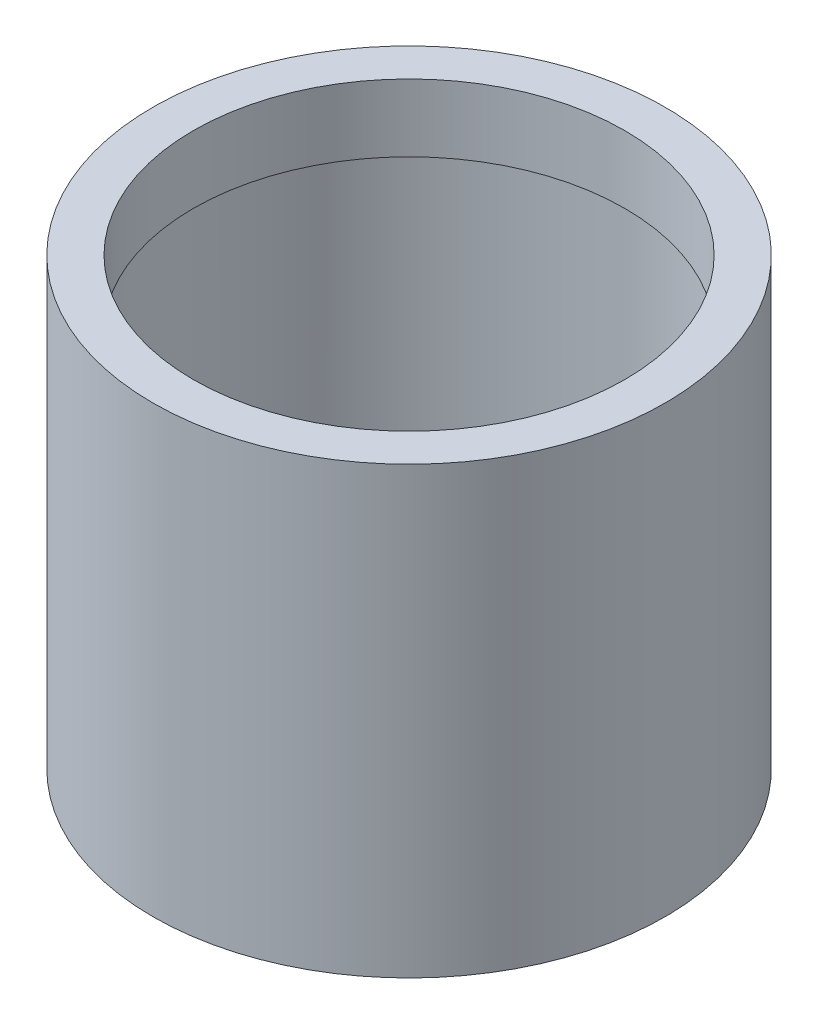
SolidWorks part; units mm, degrees
ref_plane "Спереди" through (0, 0, 0) normal (0, 0, 1) x (1, 0, 0)
ref_plane "Сверху" through (0, 0, 0) normal (0, 1, 0) x (1, 0, 0)
ref_plane "Справа" through (0, 0, 0) normal (1, 0, 0) x (0, 0, -1)
sketch "Sketch1" plane through (0, 0, 0) normal (0, 1, 0) x (1, 0, 0)
  circle A0 centre (0, 0) radius 19
extrude "Boss-Extrude1" add sketch "Sketch1" along normal blind 33
sketch "Sketch2" plane through (0, 33, 0) normal (0, 1, 0) x (1, 0, 0)
  circle A0 centre (0, 0) radius 16
extrude "Cut-Extrude1" cut sketch "Sketch2" against normal blind 5
sketch "Sketch3" plane through (0, 0, 0) normal (0, -1, 0) x (1, 0, 0)
  circle A0 centre (0, 0) radius 17.5
extrude "Cut-Extrude2" cut sketch "Sketch3" against normal up to surface (28 mm away) up to face at (0, 28, 16)
